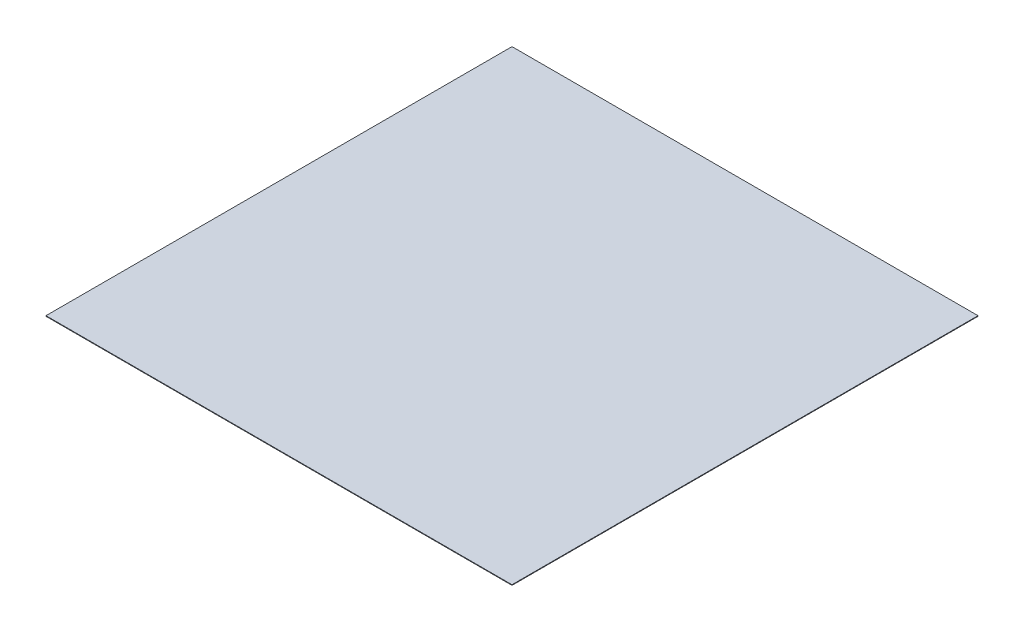
SolidWorks part; units mm, degrees
ref_plane "Front Plane" through (0, 0, 0) normal (0, 0, 1) x (1, 0, 0)
ref_plane "Top Plane" through (0, 0, 0) normal (0, 1, 0) x (1, 0, 0)
ref_plane "Right Plane" through (0, 0, 0) normal (1, 0, 0) x (0, 0, -1)
sketch "Sketch1" plane through (0, 0, 0) normal (0, 1, 0) x (1, 0, 0)
  line L1 (0, 0) -> (20320, 0)
  line L2 (0, 0) -> (0, 20320)
  line L3 (0, 20320) -> (20320, 20320)
  line L4 (20320, 0) -> (20320, 20320)
  dimension "D1" = 20320
  dimension "D2" = 20320
extrude "Extrude1" add sketch "Sketch1" along normal blind 25.4
